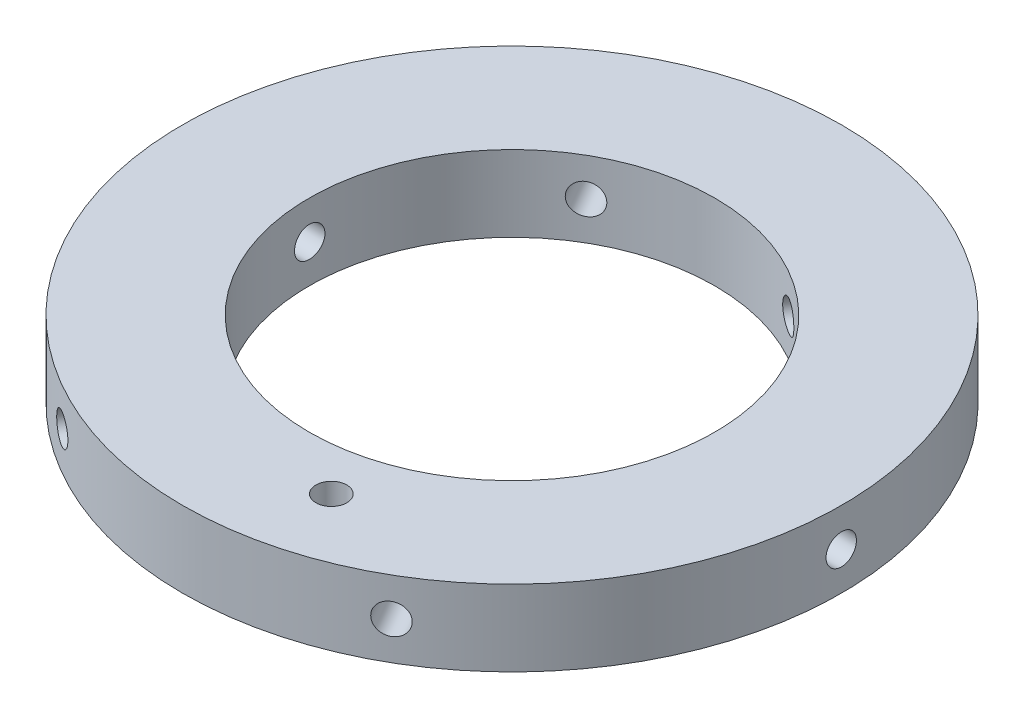
SolidWorks part; units mm, degrees
ref_plane "Front Plane" through (0, 0, 0) normal (0, 0, 1) x (1, 0, 0)
ref_plane "Top Plane" through (0, 0, 0) normal (0, 1, 0) x (1, 0, 0)
ref_plane "Right Plane" through (0, 0, 0) normal (1, 0, 0) x (0, 0, -1)
sketch "Sketch1" plane through (0, 0, 0) normal (0, 1, 0) x (1, 0, 0)
  line L0 (0, 0) -> (0, 87.698) construction
  line L1 (0, 0) -> (-128.1213, 0) construction
  circle A0 centre (0, 0) radius 65
  circle A1 centre (0, 0) radius 40
  circle A2 centre (12.723, -48.3542) radius 3.05
  dimension "D1" = 130
  dimension "D2" = 80
extrude "Boss-Extrude1" add sketch "Sketch1" along normal blind 15
sketch "Sketch2" plane through (0, 0, 0) normal (1, 0, 0) x (0, 0, -1)
  line L0 (65, 7.5) -> (-65, 7.5) construction
  line L1 (65, 0) -> (65, 15) construction
  line L2 (-65, 15) -> (-65, 0) construction
  circle A0 centre (0, 7.5) radius 3
  point P8 (0, 0)
  dimension "D1" = 6
extrude "Cut-Extrude1" cut sketch "Sketch2" against normal through all
pattern_circular "CirPattern1" count 6 over 360 about axis through (0, 15, 0) along (0, 1, 0) of "Cut-Extrude1"
equation "\"holes\"=6"
equation "\"D1@CirPattern1\"=\"holes\""
